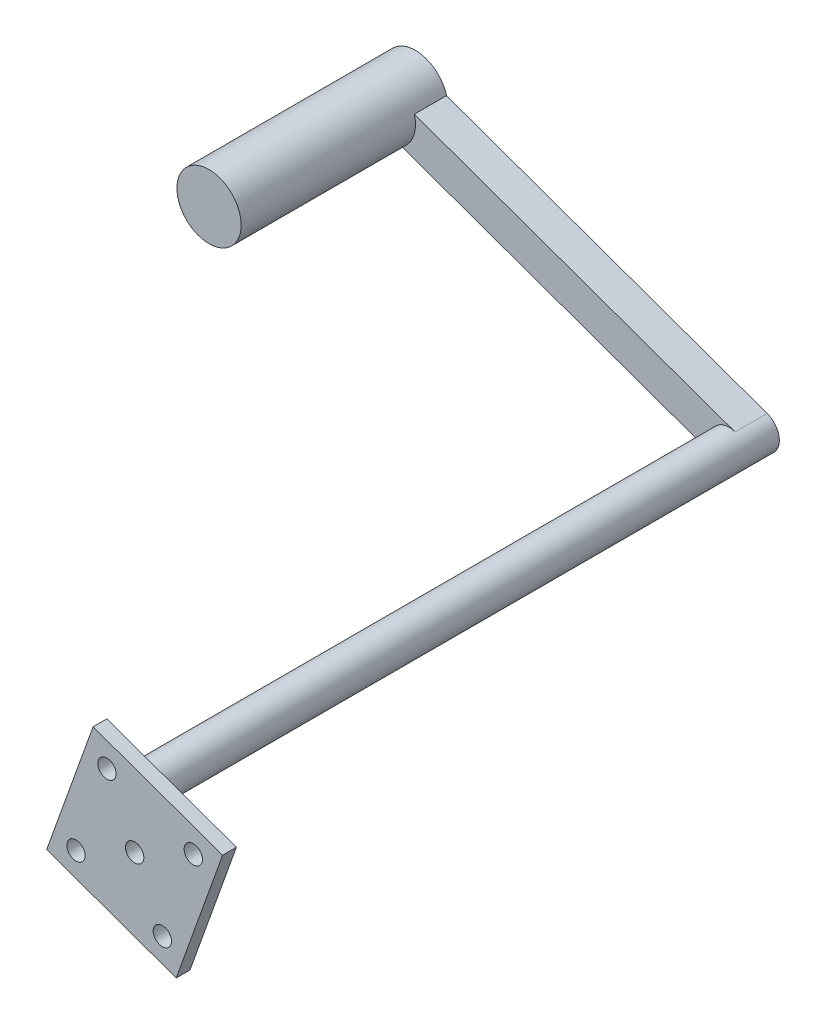
SolidWorks part; units mm, degrees
ref_plane "前视基准面" through (0, 0, 0) normal (0, 0, 1) x (1, 0, 0)
ref_plane "上视基准面" through (0, 0, 0) normal (0, 1, 0) x (1, 0, 0)
ref_plane "右视基准面" through (0, 0, 0) normal (1, 0, 0) x (0, 0, -1)
other "Configuration Table"
sketch "草图1" plane through (0, 0, 0) normal (0, 0, 1) x (1, 0, 0)
  circle A0 centre (-86.6066, -63.7835) radius 7
extrude "凸台-拉伸1" add sketch "草图1" along normal blind 45
sketch "草图3" plane through (0, 0, 0) normal (0, 0, -1) x (-1, 0, 0)
  line L0 (86.6066, -63.7835) -> (11.2929, -90.7622) construction
  line L1 (87.9556, -67.5492) -> (12.6419, -94.5278)
  line L2 (85.2577, -60.0178) -> (9.944, -86.9965)
  arc A0 (87.9556, -67.5492) -> (85.2577, -60.0178) centre (86.6066, -63.7835) ccw
  arc A1 (9.944, -86.9965) -> (12.6419, -94.5278) centre (11.2929, -90.7622) ccw
  point P2 (48.9498, -77.2728)
extrude "凸台-拉伸2" add sketch "草图3" against normal blind 7
sketch "草图7" plane through (0, 0, 7) normal (0, 0, 1) x (1, 0, 0)
  circle A3 centre (-11.2929, -90.7622) radius 4
extrude "凸台-拉伸3" add sketch "草图7" along normal blind 135
sketch "草图8" plane through (0, 0, 142) normal (0, 0, 1) x (1, 0, 0)
  line L0 (-12.6419, -94.5278) -> (-82.5475, -69.4865) construction
  line L3 (-11.2929, -90.7622) -> (22.1323, -102.7356) construction
  line L4 (-11.883, -74.6174) -> (16.3597, -84.7344)
  line L5 (16.3597, -84.7344) -> (6.2427, -112.9771)
  line L6 (-9.944, -86.9965) -> (-12.6419, -94.5278) construction
  line L7 (6.2427, -112.9771) -> (-22, -102.8601)
  line L8 (-22, -102.8601) -> (-11.883, -74.6174)
  circle A0 centre (-8.862, -81.0107) radius 2
  circle A1 centre (9.9664, -87.7554) radius 2
  circle A3 centre (-15.6067, -99.8391) radius 2
  circle A4 centre (3.2217, -106.5838) radius 2
  circle A5 centre (-2.8202, -93.7973) radius 2
  dimension "D1" = 30
  dimension "D2" = 30
  dimension "D5" = 5
  dimension "D10" = 5
  dimension "D11" = 15
  dimension "D3" = 5
  dimension "D4" = 5
  dimension "D6" = 5
  dimension "D7" = 5
  dimension "D8" = 5
  dimension "D9" = 5
  dimension "D12" = 15
  dimension "D13" = 9
extrude "凸台-拉伸4" add sketch "草图8" along normal blind 3
